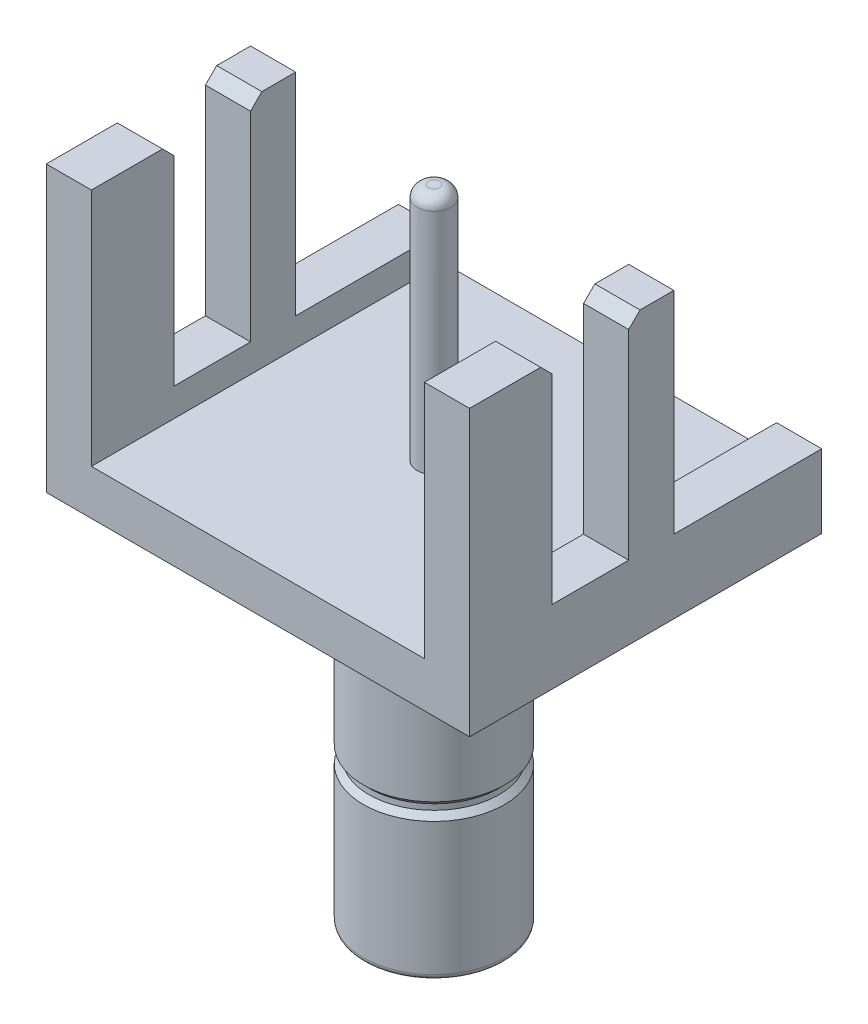
SolidWorks part; units mm, degrees
ref_plane "Front Plane" through (0, 0, 0) normal (0, 0, 1) x (1, 0, 0)
ref_plane "Top Plane" through (0, 0, 0) normal (0, 1, 0) x (1, 0, 0)
ref_plane "Right Plane" through (0, 0, 0) normal (1, 0, 0) x (0, 0, -1)
sketch "Sketch1" plane through (0, 0, 0) normal (0, 1, 0) x (1, 0, 0)
  line L1 (-4.7625, -3.9624) -> (4.7625, -3.9624)
  line L2 (-4.7625, -3.9624) -> (-4.7625, 3.9624)
  line L3 (-4.7625, 3.9624) -> (4.7625, 3.9624)
  line L4 (4.7625, -3.9624) -> (4.7625, 3.9624)
  line L5 (-4.7625, -3.9624) -> (4.7625, 3.9624) construction
  line L6 (-4.7625, 3.9624) -> (4.7625, -3.9624) construction
  point P0 (0, 0)
  dimension "D1" = 9.525
  dimension "D2" = 7.9248
extrude "Boss-Extrude1" add sketch "Sketch1" along normal blind 1.016
sketch "Sketch2" plane through (0, 1.016, 0) normal (0, 1, 0) x (1, 0, 0)
  line L0 (-4.7625, -3.9624) -> (4.7625, -3.9624) construction
  line L1 (-4.7625, 3.9624) -> (-3.7465, 3.9624)
  line L2 (-4.7625, 3.9624) -> (-4.7625, -3.9624)
  line L3 (-4.7625, -3.9624) -> (-3.7465, -3.9624)
  line L4 (-3.7465, 3.9624) -> (-3.7465, -3.9624)
  line L6 (4.7625, 3.9624) -> (3.7465, 3.9624)
  line L7 (4.7625, 3.9624) -> (4.7625, -3.9624)
  line L8 (4.7625, -3.9624) -> (3.7465, -3.9624)
  line L9 (3.7465, 3.9624) -> (3.7465, -3.9624)
  dimension "D1" = 1.016
extrude "Boss-Extrude2" add sketch "Sketch2" along normal blind 0.635
sketch "Sketch3" plane through (0, 1.651, 0) normal (0, 1, 0) x (1, 0, 0)
  line L0 (-3.7465, -3.9624) -> (-3.7465, 3.9624) construction
  line L1 (-4.7625, -3.9624) -> (-3.7465, -3.9624)
  line L2 (-4.7625, -3.9624) -> (-4.7625, -2.1082)
  line L3 (-4.7625, -2.1082) -> (-3.7465, -2.1082)
  line L4 (-3.7465, -3.9624) -> (-3.7465, -2.1082)
  line L5 (-4.7625, 3.9624) -> (-4.7625, -3.9624) construction
  line L6 (-4.7625, 0.635) -> (-3.7465, 0.635)
  line L7 (-4.7625, 0.635) -> (-4.7625, -0.381)
  line L8 (-4.7625, -0.381) -> (-3.7465, -0.381)
  line L9 (-3.7465, 0.635) -> (-3.7465, -0.381)
  line L10 (0, 0) -> (0, -3.9624) construction
  line L11 (-3.7465, -3.9624) -> (3.7465, -3.9624) construction
  line L12 (3.7465, 0.635) -> (3.7465, -0.381)
  line L13 (4.7625, -0.381) -> (3.7465, -0.381)
  line L14 (4.7625, 0.635) -> (4.7625, -0.381)
  line L15 (4.7625, 0.635) -> (3.7465, 0.635)
  line L16 (3.7465, -3.9624) -> (3.7465, -2.1082)
  line L17 (4.7625, -2.1082) -> (3.7465, -2.1082)
  line L18 (4.7625, -3.9624) -> (4.7625, -2.1082)
  line L19 (4.7625, -3.9624) -> (3.7465, -3.9624)
  dimension "D1" = 1.8542
  dimension "D2" = 1.7272
  dimension "D3" = 1.016
extrude "Boss-Extrude3" add sketch "Sketch3" along normal blind 4.7498
chamfer "Chamfer1" distance 0.254 angle 45 4 edges at (-4.2545, 6.4008, 2.1082) (4.2545, 6.4008, 2.1082) (4.2545, 6.4008, 0.381) (-4.2545, 6.4008, 0.381)
sketch "Sketch4" plane through (0, 1.016, 0) normal (0, 1, 0) x (1, 0, 0)
  circle A0 centre (0, 0) radius 0.381
  dimension "D1" = 0.762
extrude "Boss-Extrude4" add sketch "Sketch4" along normal up to surface (5.3848 mm away) up to face at (-4.2545, 6.4008, -0.254)
fillet "Fillet1" radius 0.254 1 edges at (0, 6.4008, 0.381)
sketch "Sketch5" plane through (0, 0, 0) normal (0, -1, 0) x (1, 0, 0)
  circle A0 centre (0, 0) radius 0.381
  circle A1 centre (0, 0) radius 1.27
  circle A2 centre (0, 0) radius 1.5875
  dimension "D1" = 0.762
  dimension "D2" = 3.175
  dimension "D3" = 0.3175
extrude "Boss-Extrude5" add sketch "Sketch5" along normal blind 8.001 contours A2 A1 | A0
sketch "Sketch6" plane through (0, 0, 0) normal (1, 0, 0) x (0, 0, -1)
  line L0 (1.5875, -4.5085) -> (1.4605, -4.6355)
  line L1 (1.5875, -8.001) -> (1.5875, 0) construction
  line L2 (1.4605, -4.6355) -> (1.4605, -4.7625)
  line L3 (1.4605, -4.7625) -> (1.5875, -4.8895)
  line L4 (1.5875, -4.8895) -> (1.5875, -4.5085)
  line L5 (1.4605, -4.699) -> (1.5875, -4.699) construction
  line L6 (-1.5875, -8.001) -> (1.5875, -8.001) construction
  dimension "D1" = 45
  dimension "D2" = 0.127
  dimension "D3" = 0.127
  dimension "D4" = 3.302
ref_axis "Axis1" through (0, -8.001, 0) along (0, 1, 0)
revolve "Cut-Revolve1" cut sketch "Sketch6" angle 360 about axis through (0, -8.001, 0) along (0, 1, 0)
sketch "Sketch7" plane through (0, -8.001, 0) normal (0, -1, 0) x (1, 0, 0)
  circle A1 centre (0, 0) radius 0.381
  circle A2 centre (0, 0) radius 0.381
  dimension "D1" = 0
extrude "Cut-Extrude1" cut sketch "Sketch7" against normal blind 1.524
sketch "Sketch8" plane through (0, -6.477, 0) normal (0, -1, 0) x (1, 0, 0)
  circle A1 centre (0, 0) radius 0.381
  circle A2 centre (0, 0) radius 0.381
  dimension "D1" = 0
extrude "Boss-Extrude6" add sketch "Sketch8" along normal blind 0.762 draft 15
fillet "Fillet2" radius 0.127 1 edges at (0, -7.239, -0.1768)
fillet "Fillet3" radius 0.127 1 edges at (0, -8.001, -1.5875)
